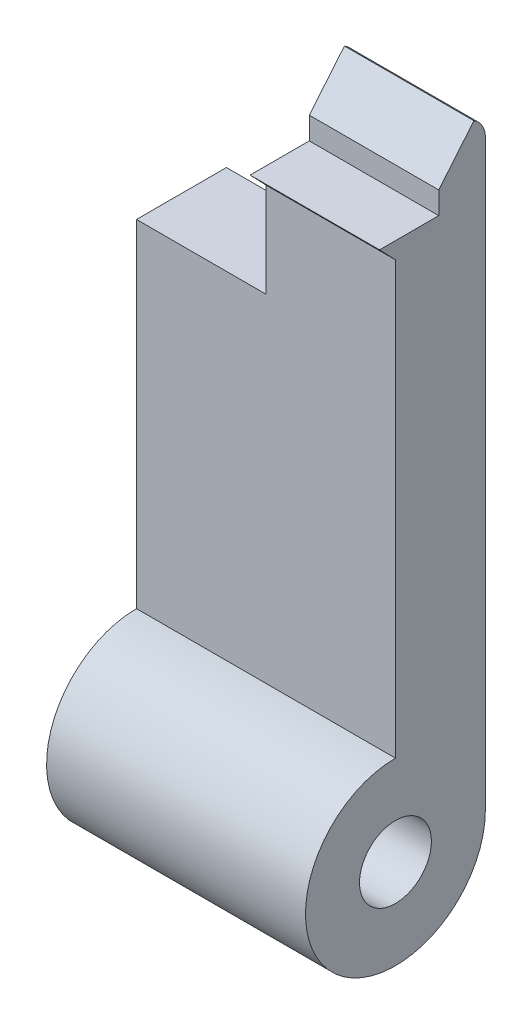
SolidWorks part; units mm, degrees
ref_plane "Front Plane" through (0, 0, 0) normal (0, 0, 1) x (1, 0, 0)
ref_plane "Top Plane" through (0, 0, 0) normal (0, 1, 0) x (1, 0, 0)
ref_plane "Right Plane" through (0, 0, 0) normal (1, 0, 0) x (0, 0, -1)
sketch "Sketch2" plane through (0, 0, 0) normal (1, 0, 0) x (0, 0, -1)
  line L0 (3.175, 0) -> (3.175, 20.574)
  line L1 (0, 3.175) -> (0, 18.415)
  line L2 (1.5299, 19.001) -> (1.5299, 20.574)
  line L3 (1.5299, 18.415) -> (-0.5614, 18.415)
  line L4 (1.5299, 18.415) -> (1.5299, 19.001)
  line L5 (1.5299, 19.001) -> (-0.5614, 19.001)
  line L6 (-0.5614, 18.415) -> (-0.5614, 19.001)
  line L7 (0, 18.415) -> (-0.5614, 19.001)
  line L8 (2.7705, 21.2824) -> (1.5299, 19.7875)
  circle A0 centre (0, 0) radius 1.27
  circle A1 centre (0, 0) radius 3.175
  arc A2 (1.5299, 20.574) -> (3.175, 20.574) centre (2.3524, 20.574) cw
  dimension "D1" = 2.54
  dimension "D2" = 6.35
  dimension "D3" = 15.24
  dimension "D4" = 20.574
extrude "Boss-Extrude1" add sketch "Sketch2" along normal blind 9.144 contours A2 L2 L4 L3 L1 A1 L0 | A1 A0 | L7 L3 L4 L5
sketch "Sketch3" plane through (0, 0, -3.175) normal (0, 0, -1) x (-1, 0, 0)
  line L0 (0, 0) -> (0, 20.574) construction
  line L1 (-4.572, 22.5862) -> (0, 22.5862)
  line L2 (-4.572, 22.5862) -> (-4.572, 15.0776)
  line L3 (-4.572, 15.0776) -> (0, 15.0776)
  line L4 (0, 22.5862) -> (0, 15.0776)
  dimension "D1" = 4.572
extrude "Cut-Extrude2" cut sketch "Sketch3" against normal through all
